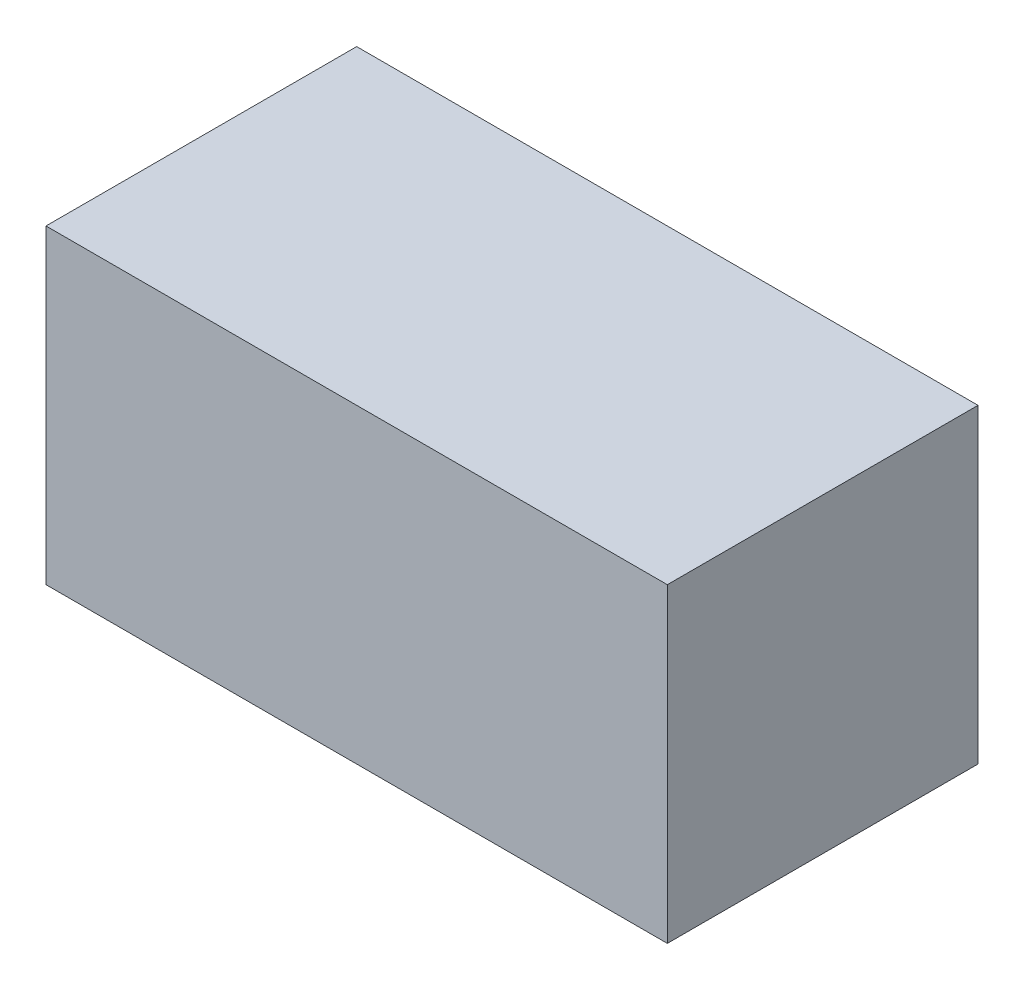
SolidWorks part; units mm, degrees
material "Maple"
ref_plane "Front Plane" through (0, 0, 0) normal (0, 0, 1) x (1, 0, 0)
ref_plane "Top Plane" through (0, 0, 0) normal (0, 1, 0) x (1, 0, 0)
ref_plane "Right Plane" through (0, 0, 0) normal (1, 0, 0) x (0, 0, -1)
sketch "Sketch1" plane through (0, 0, 0) normal (0, 1, 0) x (1, 0, 0)
  line L1 (-50.8, -25.4) -> (50.8, -25.4)
  line L2 (-50.8, -25.4) -> (-50.8, 25.4)
  line L3 (-50.8, 25.4) -> (50.8, 25.4)
  line L4 (50.8, -25.4) -> (50.8, 25.4)
  line L5 (-50.8, -25.4) -> (50.8, 25.4) construction
  line L6 (-50.8, 25.4) -> (50.8, -25.4) construction
  point P0 (0, 0)
  dimension "D1" = 101.6
  dimension "D2" = 50.8
extrude "Boss-Extrude1" add sketch "Sketch1" against normal blind 50.8
